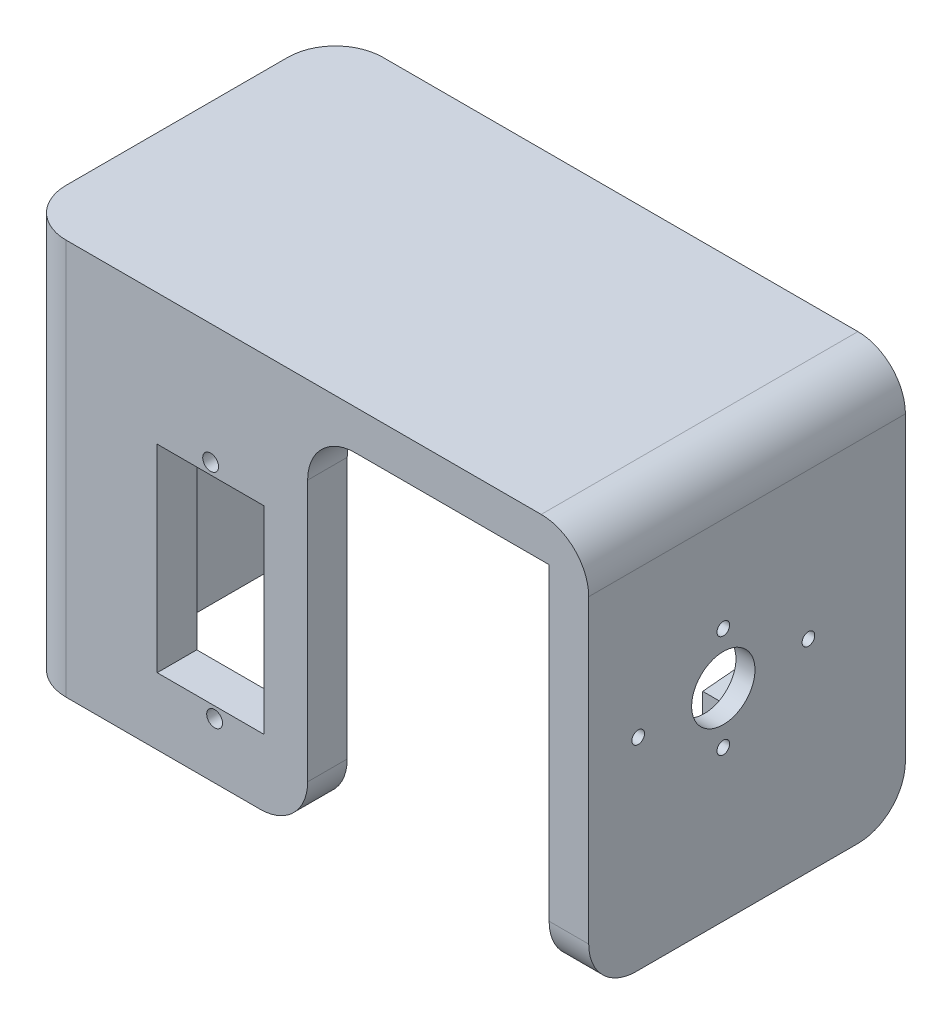
SolidWorks part; units mm, degrees
ref_plane "前视基准面" through (0, 0, 0) normal (0, 0, 1) x (1, 0, 0)
ref_plane "上视基准面" through (0, 0, 0) normal (0, 1, 0) x (1, 0, 0)
ref_plane "右视基准面" through (0, 0, 0) normal (1, 0, 0) x (0, 0, -1)
sketch "草图1" plane through (0, 0, 0) normal (0, 0, 1) x (1, 0, 0)
  line L0 (12.981, 56.4717) -> (12.981, 11.4717)
  line L1 (12.981, 11.4717) -> (17.981, 11.4717)
  line L2 (17.981, 11.4717) -> (17.981, 61.4717)
  line L3 (17.981, 61.4717) -> (-54.019, 61.4717)
  line L5 (-49.5543, 56.4717) -> (12.981, 56.4717)
  line L7 (-49.5543, 56.4717) -> (-54.019, 56.4717)
  line L8 (-54.019, 61.4717) -> (-54.019, 56.4717)
  dimension "D1" = 90
  dimension "D2" = 5
  dimension "D3" = 5
  dimension "D4" = 72
  dimension "D5" = 50
extrude "凸台-拉伸1" add sketch "草图1" along normal blind 40
fillet "圆角2" radius 6 1 edges at (17.981, 61.4717, 20)
fillet "圆角3" radius 6 1 edges at (15.481, 11.4717, 0)
fillet "圆角4" radius 6 1 edges at (15.481, 11.4717, 40)
fillet "圆角5" radius 6 1 edges at (-54.019, 58.9717, 0)
fillet "圆角6" radius 6 1 edges at (-54.019, 58.9717, 40)
sketch "草图2" plane through (12.981, 0, 0) normal (-1, 0, 0) x (0, 0, 1)
  line L10 (25.4, 43.4282) -> (25.4, 40.1179)
  line L11 (37.1158, 39.4558) -> (25.4, 40.1179)
  line L12 (37.1158, 34.5007) -> (25.4, 33.8386)
  line L13 (25.4, 33.8386) -> (25.4, 30.5282)
  line L14 (20.6, 32.9212) -> (20.6, 30.5282)
  line L15 (5.9039, 34.244) -> (20.6, 32.9212)
  line L16 (5.9039, 39.7125) -> (20.6, 41.0352)
  line L17 (20.6, 43.4282) -> (20.6, 41.0352)
  arc A12 (37.1158, 34.5007) -> (37.1158, 39.4558) centre (37.45, 36.9782) ccw
  arc A14 (25.4, 30.5282) -> (20.6, 30.5282) centre (23, 30.5282) cw
  arc A15 (5.9039, 39.7125) -> (5.9039, 34.244) centre (6.15, 36.9782) ccw
  arc A16 (25.4, 43.4282) -> (20.6, 43.4282) centre (23, 43.4282) ccw
  point P17 (21.1, 36.9782)
  point P19 (24.9, 36.9782)
  point P22 (23, 33.5282)
extrude "切除-拉伸1" cut sketch "草图2" against normal blind 2.6
sketch "草图3" plane through (0, 56.4717, 0) normal (0, -1, 0) x (1, 0, 0)
  line L0 (-54.019, 34) -> (-54.019, 6)
  line L1 (-48.019, 40) -> (-17.519, 40)
  line L2 (-48.019, 40) -> (12.981, 40) construction
  line L3 (-54.019, 6) -> (-49.019, 6)
  line L4 (-49.019, 6) -> (-49.019, 29)
  line L5 (-43.019, 35) -> (-17.519, 35)
  line L6 (-17.519, 35) -> (-17.519, 40)
  arc A0 (-48.019, 40) -> (-54.019, 34) centre (-48.019, 34) ccw
  arc A1 (-43.019, 35) -> (-49.019, 29) centre (-43.019, 29) ccw
  dimension "D3" = 6
  dimension "D1" = 5
  dimension "D2" = 5
extrude "凸台-拉伸2" add sketch "草图3" along normal blind 45
sketch "草图4" plane through (0, 0, 40) normal (0, 0, 1) x (1, 0, 0)
  line L0 (-23.019, 32.4085) -> (-21.5424, 32.4085) construction
  line L1 (-14.769, 11.4717) -> (-14.769, 1.1207) construction
  line L2 (-23.019, 19.9085) -> (-36.519, 19.9085)
  line L3 (-36.519, 19.9085) -> (-36.519, 44.9085)
  line L4 (-36.519, 44.9085) -> (-23.019, 44.9085)
  line L5 (-29.769, 46.304) -> (-29.769, 42.4008) construction
  line L6 (-23.019, 19.9085) -> (-23.019, 44.9085)
  circle A4 centre (-29.269, 18.5085) radius 1
  circle A5 centre (-29.769, 46.304) radius 1
  point P15 (-29.769, 19.9085)
  point P16 (-29.769, 44.9085)
  dimension "D3" = 27.8
  dimension "D5" = 2
  dimension "D6" = 2
  dimension "D1" = 25
  dimension "D2" = 13.5
  dimension "D4" = 13.9
extrude "切除-拉伸2" cut sketch "草图4" against normal blind 60
fillet "圆角7" radius 6 1 edges at (-17.519, 11.4717, 37.5)
fillet "圆角8" radius 6 1 edges at (-17.519, 56.4717, 37.5)
sketch "草图5" plane through (15.581, 0, 0) normal (-1, 0, 0) x (0, 0, 1)
  line L0 (16.55, 36.9782) -> (29.45, 36.9782) construction
  line L1 (23, 22.5282) -> (23, 53.8282) construction
  line L2 (6.15, 36.9782) -> (41.0957, 36.9782) construction
  line L3 (23, 42.794) -> (23, 24.9781) construction
  circle A0 centre (12.25, 36.9782) radius 0.8
  circle A1 centre (23, 36.9782) radius 4
  circle A2 centre (33.75, 36.9782) radius 0.8
  circle A3 centre (23, 30.4782) radius 0.8
  circle A4 centre (23, 43.4782) radius 0.8
  dimension "D1" = 21.5
  dimension "D2" = 13
  dimension "D3" = 8
extrude "切除-拉伸3" cut sketch "草图5" against normal blind 10
ref_plane "基准面1" through (0, 0, 20) normal (0, 0, -1) x (-1, 0, 0)
sketch "草图7" plane through (0, 0, 0) normal (0, 0, -1) x (-1, 0, 0)
  line L0 (-17.981, 17.4717) -> (-17.981, 55.4717) construction
  line L1 (-11.981, 61.4717) -> (48.019, 61.4717) construction
  line L2 (-17.981, 31.4717) -> (-17.981, 55.4717)
  line L3 (-11.981, 61.4717) -> (48.019, 61.4717)
  line L4 (-17.981, 31.4717) -> (12.019, 31.4717)
  line L5 (12.019, 31.4717) -> (12.019, 61.4717)
  arc A0 (-11.981, 61.4717) -> (-17.981, 55.4717) centre (-11.981, 55.4717) ccw construction
  arc A1 (-11.981, 61.4717) -> (-17.981, 55.4717) centre (-11.981, 55.4717) ccw
  dimension "D1" = 30
  dimension "D2" = 30
extrude "凸台-拉伸4" add sketch "草图7" against normal blind 2.5
fillet "圆角9" radius 5 1 edges at (-12.019, 31.4717, 1.25)
